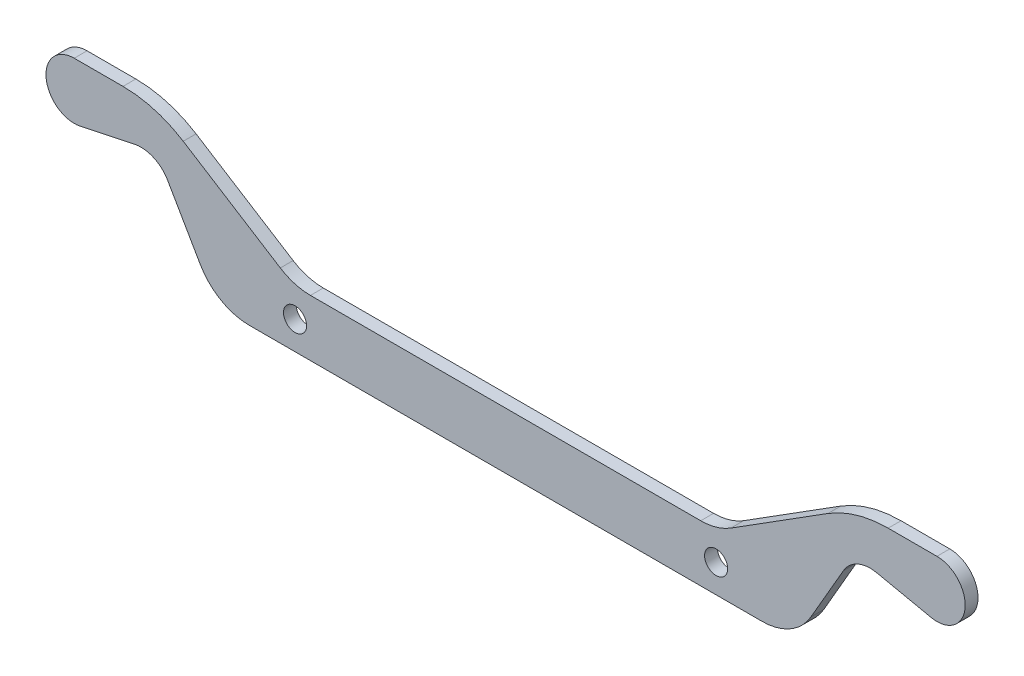
SolidWorks part; units mm, degrees
ref_plane "Front Plane" through (0, 0, 0) normal (0, 0, 1) x (1, 0, 0)
ref_plane "Top Plane" through (0, 0, 0) normal (0, 1, 0) x (1, 0, 0)
ref_plane "Right Plane" through (0, 0, 0) normal (1, 0, 0) x (0, 0, -1)
sketch "Sketch1" plane through (0, 0, 0) normal (0, 0, 1) x (1, 0, 0)
  line L0 (0, 0) -> (-49.9267, 0)
  line L1 (0, 0) -> (0, 11)
  line L2 (0, 11) -> (-38, 11)
  line L3 (0, 11) -> (0, 22) construction
  line L4 (0, 22) -> (-38, 22) construction
  line L5 (-38, 22) -> (-38, 22.5) construction
  line L6 (-83.9973, 28) -> (-74.5, 28)
  line L7 (-59.453, 5.5) -> (-65.8038, 16.5)
  line L8 (-38, 22.5) -> (-83.9973, 22.5) construction
  line L9 (-43.8662, 12.6947) -> (-62.7676, 24.6105)
  line L10 (-83.9973, 17) -> (-83.9973, 28) construction
  line L11 (-82.8566, 17.1196) -> (-72.2444, 19.3695)
  line L12 (0, 5.5) -> (-41, 5.5) construction
  arc A0 (-43.8662, 12.6947) -> (-38, 11) centre (-38, 22) ccw
  arc A1 (-82.8566, 17.1196) -> (-83.9973, 28) centre (-83.9973, 22.5) cw
  arc A2 (-65.8038, 16.5) -> (-72.2444, 19.3695) centre (-71, 13.5) ccw
  arc A3 (-62.7676, 24.6105) -> (-74.5, 28) centre (-74.5, 6) ccw
  circle A4 centre (-41, 5.5) radius 2.25
  arc A5 (-49.9267, 0) -> (-59.453, 5.5) centre (-49.9267, 11) cw
  dimension "D5" = 5.5
  dimension "D9" = 6
  dimension "D11" = 22
  dimension "D13" = 4.5
  dimension "D15" = 11
  dimension "D1" = 11
  dimension "D2" = 11
  dimension "D3" = 38
  dimension "D4" = 46
  dimension "D6" = 60
  dimension "D7" = 71
  dimension "D8" = 13.5
  dimension "D10" = 0.5
  dimension "D12" = 74.5
  dimension "D14" = 41
extrude "Boss-Extrude1" add sketch "Sketch1" along normal blind 2.5
mirror "Mirror1" about plane through (0, 0, 2.5) normal (-1, 0, 0) of bodies 101
